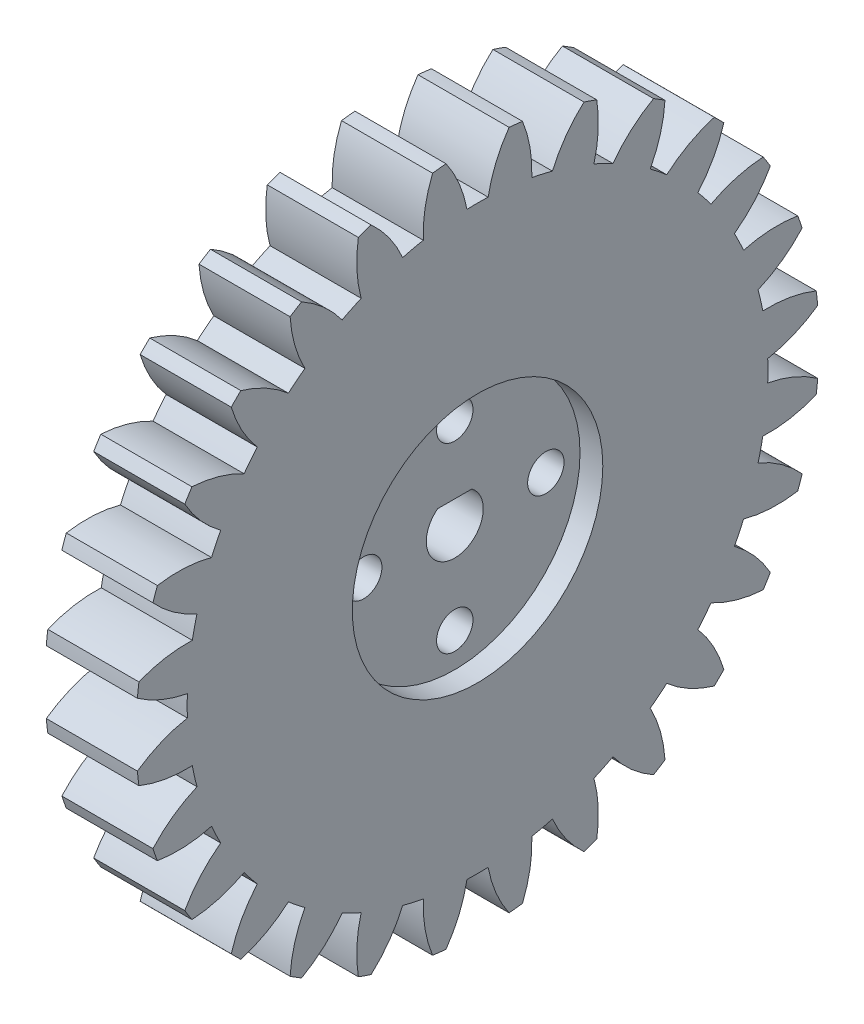
SolidWorks part; units mm, degrees
material "ABS"
ref_plane "Plane1" through (0, 0, 0) normal (0, 0, 1) x (1, 0, 0)
ref_plane "Plane2" through (0, 0, 0) normal (0, 1, 0) x (1, 0, 0)
ref_plane "Plane3" through (0, 0, 0) normal (1, 0, 0) x (0, 0, -1)
sketch "HoldingSke" plane through (0, 0, 0) normal (0, 1, 0) x (1, 0, 0)
  line L0 (0, 0) -> (0.4415, -0.2347)
  line L1 (-15, 0) -> (100, 0) construction
  line L2 (0, 0) -> (-2.1039, 2.3779)
  line L3 (0, 0) -> (-11.863, 4.5341)
  line L4 (0, 0) -> (7.6251, 4.0544)
  line L5 (0, 0) -> (-46.8476, -17.4728)
  line L6 (0, 0) -> (-9.9476, -6.7116)
  line L7 (-2.1039, 2.3779) -> (8.6586, 51.2059)
  line L8 (-76.2, 54.61) -> (-76.1, 54.61)
  line L9 (-71.009, 38.7566) -> (-53.1078, 45.2721)
  line L10 (-76.2, 71.12) -> (104.1128, 71.12)
  line L11 (0, 0) -> (-12, 0)
  line L12 (-76.2, 101.6) -> (-76.133, 101.6)
  line L13 (24.9733, 27.94) -> (52.9518, 28.4284)
  line L14 (24.9733, 27.94) -> (24.9743, 27.94)
  line L15 (24.9733, 27.94) -> (100.4006, 29.5858)
  line L16 (-63.627, -2) -> (-12.827, -2)
  circle A0 centre (0, 0) radius 0.1
  circle A1 centre (0, 0) radius 25.499
  circle A2 centre (0, 0) radius 37.5
  circle A3 centre (0, 0) radius 0.1
  dimension "MHD" = 50.998
  dimension "Hub_dia" = 75
  dimension "Bore" = 0.2
  dimension "MBD" = 0.2
  dimension "Num_teeth" = 28
  dimension "Pitch" = 0.5
  dimension "Overall_len" = 50
  dimension "Show_teeth" = 28
  dimension "Thickness" = 12
  dimension "OAL" = 50.0001
  dimension "T_dim" = 0.1
  dimension "Ap" = 20
  dimension "H" = 19.05
  dimension "Pitch_radius" = 180.3128
  dimension "Width" = 12
  dimension "Backlash" = 0.067
  dimension "Addendum_fac" = 1
  dimension "Dedendum_fac" = 1.25
  dimension "Clearance_fac" = 0.25
  dimension "Dedendum_add" = 0.001
  dimension "Module" = 2
sketch "BasProSke" plane through (0, 0, 0) normal (0, 1, 0) x (1, 0, 0)
  line L0 (-10, 0) -> (60, 0) construction
  line L1 (0, 0) -> (0, 30)
  line L2 (0, 0) -> (8, 0)
  line L3 (8, 0) -> (8, 30)
  line L4 (8, 30) -> (0, 30)
  dimension "Thickness" = 8
  dimension "Diameter" = 60
revolve "Base-Revolve" add sketch "BasProSke" angle 360 about L0
sketch "TooCutSke" plane through (0, 0, 0) normal (1, 0, 0) x (0, 0, -1)
  line L1 (0, 0) -> (0, 107) construction
  line L2 (0, 0) -> (-1.6872, 27.9491) construction
  line L3 (0, 0) -> (-6.2616, 55.5729) construction
  line L4 (-1.6872, 27.9491) -> (-3.1308, 27.7865) construction
  arc A0 (0.9285, 25.4821) -> (-0.9285, 25.4821) centre (0, 0) ccw
  arc A1 (2.7859, 29.8959) -> (-2.7859, 29.8959) centre (0, 0) ccw
  circle A2 centre (0, 0) radius 28 construction
  circle A3 centre (0, 0) radius 26.3114 construction
  arc A4 (-0.9285, 25.4821) -> (-2.7859, 29.8959) centre (-11.9418, 23.4453) ccw
  arc A5 (2.7859, 29.8959) -> (0.9285, 25.4821) centre (11.9418, 23.4453) ccw
  dimension "Root_dia" = 50.998
  dimension "Overcut_dia" = 60.0508
  dimension "Pitch_dia" = 56
  dimension "Base_dia" = 52.6228
  dimension "Flank_rad" = 11.2
  dimension "Half_ang" = 6.429
  dimension "Half_CT" = 1.4527
extrude "ToothCut" cut sketch "TooCutSke" along normal through all
fillet "Breaks" [suppressed] radius 0.04
fillet "RootFillets" [suppressed] radius 0.501
pattern_circular "TeethCuts" count 28 every 12.857 about axis through (-10, 0, 0) along (1, 0, 0) of "ToothCut", "RootFillets", "Breaks"
sketch "HubNeaOneSke" plane through (0, 0, 0) normal (-1, 0, 0) x (0, 0, 1)
  circle A0 centre (0, 0) radius 25.499
  dimension "Diameter" = 50.998
extrude "HubNearOne" [suppressed] add sketch "HubNeaOneSke" along normal blind 42.0001
sketch "HubNeaBotSke" plane through (0, 0, 0) normal (-1, 0, 0) x (0, 0, 1)
  circle A0 centre (0, 0) radius 25.499
  dimension "Diameter" = 50.998
extrude "HubNearBoth" [suppressed] add sketch "HubNeaBotSke" along normal blind 21
ref_plane "FarPln" through (8, 0, 0) normal (1, 0, 0) x (0, 0, -1)
sketch "HubFarSke" plane through (8, 0, 0) normal (1, 0, 0) x (0, 0, -1)
  circle A0 centre (0, 0) radius 25.499
  dimension "Diameter" = 50.998
extrude "HubFar" [suppressed] add sketch "HubFarSke" along normal blind 21
sketch "BorSke" plane through (0, 0, 0) normal (1, 0, 0) x (0, 0, -1)
  circle A0 centre (0, 0) radius 0.1
  dimension "Diameter" = 0.2
extrude "Bore" cut sketch "BorSke" along normal mid plane 100.0001
sketch "KeySke" plane through (0, 0, 0) normal (1, 0, 0) x (0, 0, -1)
  line L0 (-0.05, 0) -> (-0.05, 0.2)
  line L1 (-0.05, 0.2) -> (0.05, 0.2)
  line L2 (0.05, 0.2) -> (0.05, 0)
  line L3 (0, 0) -> (0, 34) construction
  line L4 (-0.05, 0) -> (0.05, 0)
  dimension "Offset" = 0.2
  dimension "Width" = 0.1
extrude "Keyway" [suppressed] cut sketch "KeySke" along normal mid plane 100.0001
pattern_circular "Keyway2" [suppressed] count 2 every 90 about axis through (-10, 0, 0) along (1, 0, 0)
sketch "Schizzo1" plane through (8, 0, 0) normal (1, 0, 0) x (0, 0, -1)
  line L0 (-1.5, 2) -> (1.5, 2)
  arc A0 (-1.5, 2) -> (1.5, 2) centre (0, 0) ccw
  dimension "D1" = 5
  dimension "D2" = 2
extrude "Taglio-Estrusione1" cut sketch "Schizzo1" against normal blind 30
sketch "Schizzo2" plane through (0, 0, 0) normal (-1, 0, 0) x (0, 0, 1)
  circle A0 centre (0, 0) radius 8 construction
  circle A1 centre (0, 8) radius 1.6
  circle A2 centre (8, 0) radius 1.6
  circle A3 centre (0, -8) radius 1.6
  circle A4 centre (-8, 0) radius 1.6
  dimension "D1" = 16
  dimension "D2" = 3.2
extrude "Taglio-Estrusione2" cut sketch "Schizzo2" against normal blind 10
sketch "Schizzo3" plane through (8, 0, 0) normal (1, 0, 0) x (0, 0, -1)
  circle A0 centre (0, 0) radius 11
  dimension "D1" = 22
extrude "Taglio-Estrusione3" cut sketch "Schizzo3" against normal blind 2
equation "' \"Module@HoldingSke\" = 6.35"
equation "' \"Num_teeth@HoldingSke\" = 12"
equation "' \"Ap@HoldingSke\" =  20"
equation "' \"Ap@HoldingSke\" = 20"
equation "' \"Width@HoldingSke\" = 0.5 * 25.4"
equation "' \"Hub_dia@HoldingSke\"= 1 * 25.4"
equation "' \"Hub_dia@HoldingSke\" = 1 * 25.4"
equation "' \"Overall_len@HoldingSke\" = 1.0 * 25.4"
equation "' \"Bore@HoldingSke\" = 0.75 * 25.4"
equation "' \"T_dim@HoldingSke\" = 0.1 * 25.4"
equation "' \"Width@KeySke\" = 0.25 * 25.4"
equation "' \"Show_teeth@HoldingSke\" = 13"
equation "' \"Backlash@HoldingSke\" = 0.009 * 25.4"
equation "' \"Addendum_fac@HoldingSke\" = 1.0"
equation "' \"Dedendum_fac@HoldingSke\" = 1.25"
equation "' \"Dedendum_add@HoldingSke\" = 0.00005 * 25.4"
equation "' \"Clearance_fac@HoldingSke\" = 0.25"
equation "\"Pitch@HoldingSke\" = 1 / \"Module@HoldingSke\""
equation "\"Overcut_dia@TooCutSke\" = (\"Num_teeth@HoldingSke\" + 2 * \"Addendum_fac@HoldingSke\") / \"Pitch@HoldingSke\" + 0.002 * 25.4"
equation "\"Pitch_dia@TooCutSke\" = \"Num_teeth@HoldingSke\" / \"Pitch@HoldingSke\""
equation "\"Base_dia@TooCutSke\" = \"Num_teeth@HoldingSke\" / \"Pitch@HoldingSke\" * cos((\"Ap@HoldingSke\"  * 3.14159265 / 180))"
equation "\"Root_dia@TooCutSke\" = (\"Num_teeth@HoldingSke\" + 2) / \"Pitch@HoldingSke\" - 2 * (\"Addendum_fac@HoldingSke\" + \"Dedendum_fac@HoldingSke\") / \"Pitch@HoldingSke\" - \"Dedendum_add@HoldingSke\" * 2"
equation "\"Half_ang@TooCutSke\" = 180 / \"Num_teeth@HoldingSke\""
equation "\"Half_CT@TooCutSke\" = \"Num_teeth@HoldingSke\" / \"Pitch@HoldingSke\" * sin((3.14159265 / 2 / \"Num_teeth@HoldingSke\")) / 2 - 7 * \"Backlash@HoldingSke\" / 4"
equation "\"Flank_rad@TooCutSke\" = \"Num_teeth@HoldingSke\" / \"Pitch@HoldingSke\" / 5"
equation "\"Radius@RootFillets\" = \"Clearance_fac@HoldingSke\" / \"Pitch@HoldingSke\" + \"Dedendum_add@HoldingSke\""
equation "\"Break_rad@Breaks\" = 0.02 / \"Pitch@HoldingSke\""
equation "\"Thickness@HoldingSke\" = \"Width@HoldingSke\""
equation "\"OAL@HoldingSke\" = \"Thickness@HoldingSke\""
equation "\"MHD@HoldingSke\" = (\"Num_teeth@HoldingSke\" + 2) / \"Pitch@HoldingSke\" - 2 * (\"Addendum_fac@HoldingSke\" + \"Dedendum_fac@HoldingSke\")  / \"Pitch@HoldingSke\" - \"Dedendum_add@HoldingSke\" * 2"
equation "\"MBD@HoldingSke\" = (\"Num_teeth@HoldingSke\" + 2) / \"Pitch@HoldingSke\" - 2 * (\"Addendum_fac@HoldingSke\" + \"Dedendum_fac@HoldingSke\")  / \"Pitch@HoldingSke\" - \"Dedendum_add@HoldingSke\" * 2 - 0.002 * 25.4"
equation "\"MHD@HoldingSke\" = ((sgn( \"MHD@HoldingSke\" - \"Hub_dia@HoldingSke\" )-1)*( \"MHD@HoldingSke\" - \"Hub_dia@HoldingSke\" ))/-2+ \"Hub_dia@HoldingSke\""
equation "\"MBD@HoldingSke\" = ((sgn( \"MBD@HoldingSke\" - \"Bore@HoldingSke\" )-1)*( \"MBD@HoldingSke\" - \"Bore@HoldingSke\" ))/-2+ \"Bore@HoldingSke\""
equation "\"OAL@HoldingSke\" = ((sgn( \"OAL@HoldingSke\" - \"Overall_len@HoldingSke\" )+1)*( \"OAL@HoldingSke\" - \"Overall_len@HoldingSke\" ))/2 + \"Overall_len@HoldingSke\" + 0.000002 * 25.4"
equation "\"Num_teeth@TeethCuts\" = int( \"Show_teeth@HoldingSke\" ) + 1"
equation "\"Num_teeth@TeethCuts\" = ((sgn( \"Num_teeth@TeethCuts\" - \"Num_teeth@HoldingSke\" )-1)*( \"Num_teeth@TeethCuts\" - \"Num_teeth@HoldingSke\" ))/-2+ \"Num_teeth@HoldingSke\""
equation "\"Num_teeth@TeethCuts\" = ((sgn( \"Num_teeth@TeethCuts\" - 2.0)+1)*( \"Num_teeth@TeethCuts\" - 2.0))/2 +2.0"
equation "\"Angle@TeethCuts\" = 360.0 / \"Num_teeth@HoldingSke\""
equation "\"Diameter@BasProSke\" = (\"Num_teeth@HoldingSke\" + 2 * \"Addendum_fac@HoldingSke\") / \"Pitch@HoldingSke\""
equation "' \"Fillet_rad@BasProSke\" =  \"Thickness@HoldingSke\" * 0.05"
equation "' \"Fillet_rad@BasProSke\" = \"Thickness@HoldingSke\" * 0.05"
equation "\"MHD@HoldingSke\" = ((sgn( \"MHD@HoldingSke\" - \"Root_dia@TooCutSke\" )-1)*( \"MHD@HoldingSke\" - \"Root_dia@TooCutSke\" ))/-2+ \"Root_dia@TooCutSke\""
equation "\"Diameter@HubNeaOneSke\" = \"MHD@HoldingSke\""
equation "\"Length@HubNearOne\" = \"OAL@HoldingSke\" - \"Thickness@BasProSke\""
equation "\"Diameter@HubNeaBotSke\" = \"MHD@HoldingSke\""
equation "\"Length@HubNearBoth\" = ( \"OAL@HoldingSke\" - \"Thickness@BasProSke\" ) / 2.0"
equation "\"Thickness@FarPln\" = \"Thickness@BasProSke\""
equation "\"Diameter@HubFarSke\" = \"MHD@HoldingSke\""
equation "\"Length@HubFar\" = ( \"OAL@HoldingSke\" - \"Thickness@BasProSke\" ) / 2.0"
equation "\"Diameter@BorSke\" = \"MBD@HoldingSke\""
equation "\"D1@Bore\" = \"OAL@HoldingSke\" * 2.0"
equation "\"D1@Keyway\" = \"OAL@HoldingSke\" * 2.0"
equation "\"Offset@KeySke\" = \"T_dim@HoldingSke\" + \"MBD@HoldingSke\" / 2.0"
